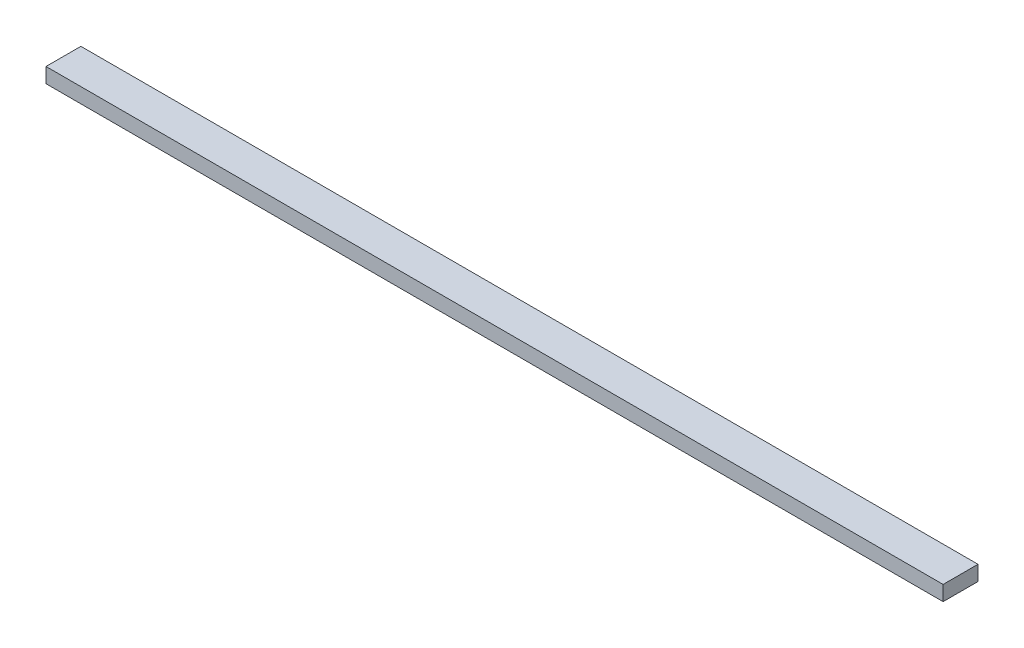
SolidWorks part; units mm, degrees
material "Pine"
ref_plane "Front Plane" through (0, 0, 0) normal (0, 0, 1) x (1, 0, 0)
ref_plane "Top Plane" through (0, 0, 0) normal (0, 1, 0) x (1, 0, 0)
ref_plane "Right Plane" through (0, 0, 0) normal (1, 0, 0) x (0, 0, -1)
sketch "Sketch2" plane through (0, 0, 0) normal (1, 0, 0) x (0, 0, -1)
  line L1 (-44.45, 19.05) -> (44.45, 19.05)
  line L2 (-44.45, 19.05) -> (-44.45, -19.05)
  line L3 (-44.45, -19.05) -> (44.45, -19.05)
  line L4 (44.45, 19.05) -> (44.45, -19.05)
  line L5 (-44.45, 19.05) -> (44.45, -19.05) construction
  line L6 (-44.45, -19.05) -> (44.45, 19.05) construction
  point P0 (0, 0)
  dimension "D1" = 88.9
  dimension "D2" = 38.1
extrude "Boss-Extrude1" add sketch "Sketch2" along normal blind 2286
sketch "Sketch3" plane through (0, 19.05, 0) normal (0, 1, 0) x (1, 0, 0)
  line L0 (0, 44.45) -> (0, -44.45) construction
  line L1 (2286, 44.45) -> (0, 44.45) construction
  line L2 (2286, -44.45) -> (0, -44.45) construction
  point P0 (25.4, 19.05)
  point P1 (25.4, -19.05)
  dimension "D1" = 25.4
  dimension "D2" = 25.4
  dimension "D3" = 25.4
  dimension "D4" = 25.4
